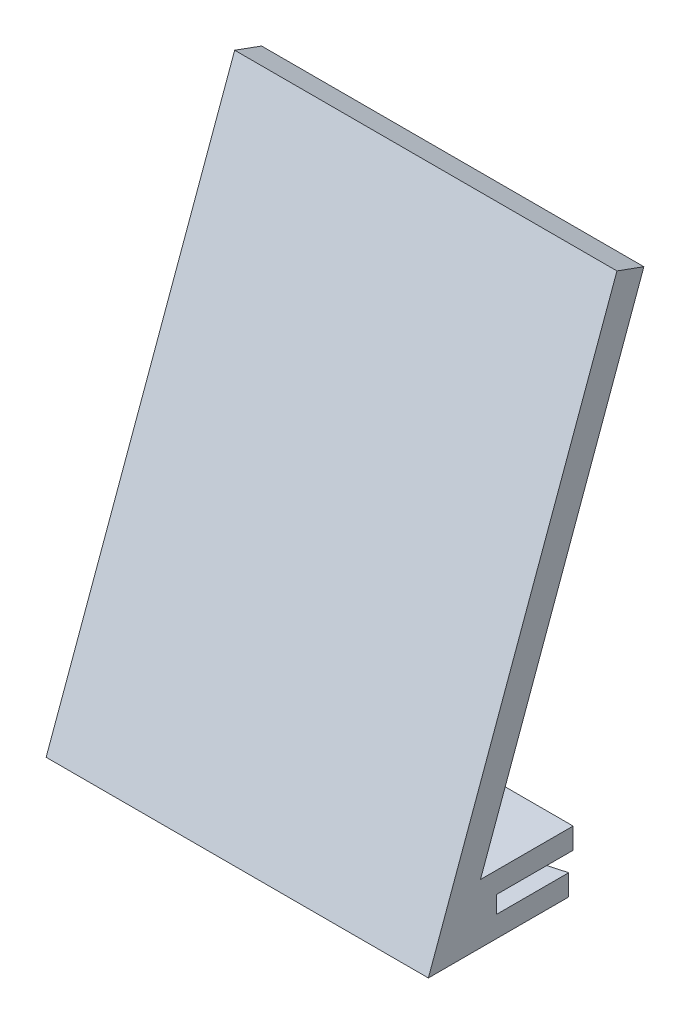
SolidWorks part; units mm, degrees
ref_plane "Alzado" through (0, 0, 0) normal (0, 0, 1) x (1, 0, 0)
ref_plane "Planta" through (0, 0, 0) normal (0, 1, 0) x (1, 0, 0)
ref_plane "Vista lateral" through (0, 0, 0) normal (1, 0, 0) x (0, 0, -1)
sketch "Croquis1" plane through (0, 0, 0) normal (0, 0, 1) x (1, 0, 0)
  line L0 (-2.6688, -78.4504) -> (-2.6688, -73.0781) construction
  line L1 (7.3312, -76.9004) -> (-12.6688, -76.9004)
  line L2 (7.3312, -76.9004) -> (7.3312, -80.0004)
  line L3 (7.3312, -80.0004) -> (-12.6688, -80.0004)
  line L4 (-12.6688, -76.9004) -> (-12.6688, -80.0004)
  line L5 (7.3312, -76.9004) -> (-12.6688, -80.0004) construction
  line L6 (7.3312, -80.0004) -> (-12.6688, -76.9004) construction
  line L7 (-2.6688, -79.7004) -> (-2.6688, -78.7004) construction
  line L8 (-1.5465, -78.7004) -> (-1.5465, -78.2004) construction
  line L9 (20.0349, -78.2004) -> (-25.3725, -78.2004) construction
  line L10 (-1.5465, -78.4504) -> (-2.6688, -78.4504) construction
  line L12 (-25.3725, -78.7004) -> (20.0349, -78.7004) construction
  line L14 (-12.6688, -78.9004) -> (7.3312, -78.9004)
  line L15 (-12.6688, -78.9004) -> (-12.6688, -78.0004)
  line L16 (-12.6688, -78.0004) -> (7.3312, -78.0004)
  line L17 (7.3312, -78.9004) -> (7.3312, -78.0004)
  line L18 (-12.6688, -78.9004) -> (7.3312, -78.0004) construction
  line L19 (-12.6688, -78.0004) -> (7.3312, -78.9004) construction
  point P0 (-2.6688, -78.4504)
  point P16 (0, 0)
  point P22 (0, 0)
  point P23 (0, 0)
  point P24 (7.3312, -77.5756)
  dimension "D1" = 1.3
  dimension "D2" = 20
  dimension "D3" = 0.2
extrude "Saliente-Extruir1" add sketch "Croquis1" against normal blind 4 contours L14 L4 L3 L2 | L4 L16 L2 L1
sketch "Croquis2" plane through (0, -80.0004, 0) normal (0, -1, 0) x (1, 0, 0)
  line L0 (15.8312, -6.742) -> (-2.6688, -1.742) construction
  line L1 (-2.6688, -1.742) -> (-21.1688, -6.742) construction
  line L2 (15.8312, -6.742) -> (-2.6688, -1.742)
  line L3 (-2.6688, -1.742) -> (-21.1688, -6.742)
  line L4 (8.1857, -4) -> (-2.6688, -1.0663)
  line L5 (7.3312, -4) -> (-12.6688, -4) construction
  line L6 (-2.6688, -1.0663) -> (-13.5233, -4)
  line L7 (-2.6688, -1.0663) -> (-2.6688, 0) construction
  line L8 (7.3312, 0) -> (-12.6688, 0) construction
  line L9 (8.1857, -4) -> (-13.5233, -4)
  point P7 (5.6857, -4)
  point P12 (5.6857, -4)
  line M6 (-12.6688, -4) -> (7.3312, -4)
  dimension "D1" = 2.5
extrude "Cortar-Extruir1" cut sketch "Croquis2" against normal up to next (1.1 mm away) contours L2 L3 M6 | L4 L6 L3 L2 M6
sketch "Croquis3" plane through (7.3312, 0, 0) normal (1, 0, 0) x (0, 0, -1)
  line L0 (0, -76.9004) -> (0, -80.0004)
  line L1 (0, -80.0004) -> (-3.5718, -80.0004)
  line L2 (-3.5718, -80.0004) -> (6.2938, -52.8951)
  line L3 (6.2938, -52.8951) -> (7.7033, -53.4081)
  line L4 (7.7033, -53.4081) -> (-0.8472, -76.9004)
  line L5 (-0.8472, -76.9004) -> (0, -76.9004)
  line L6 (4, -76.9004) -> (0, -76.9004) construction
  point P4 (-1.7172, -77.8004)
  point P9 (-2.1704, -78.1818)
  dimension "D1" = 70
  dimension "D2" = 1.5
  dimension "D3" = 25
extrude "Saliente-Extruir2" add sketch "Croquis3" against normal through all
